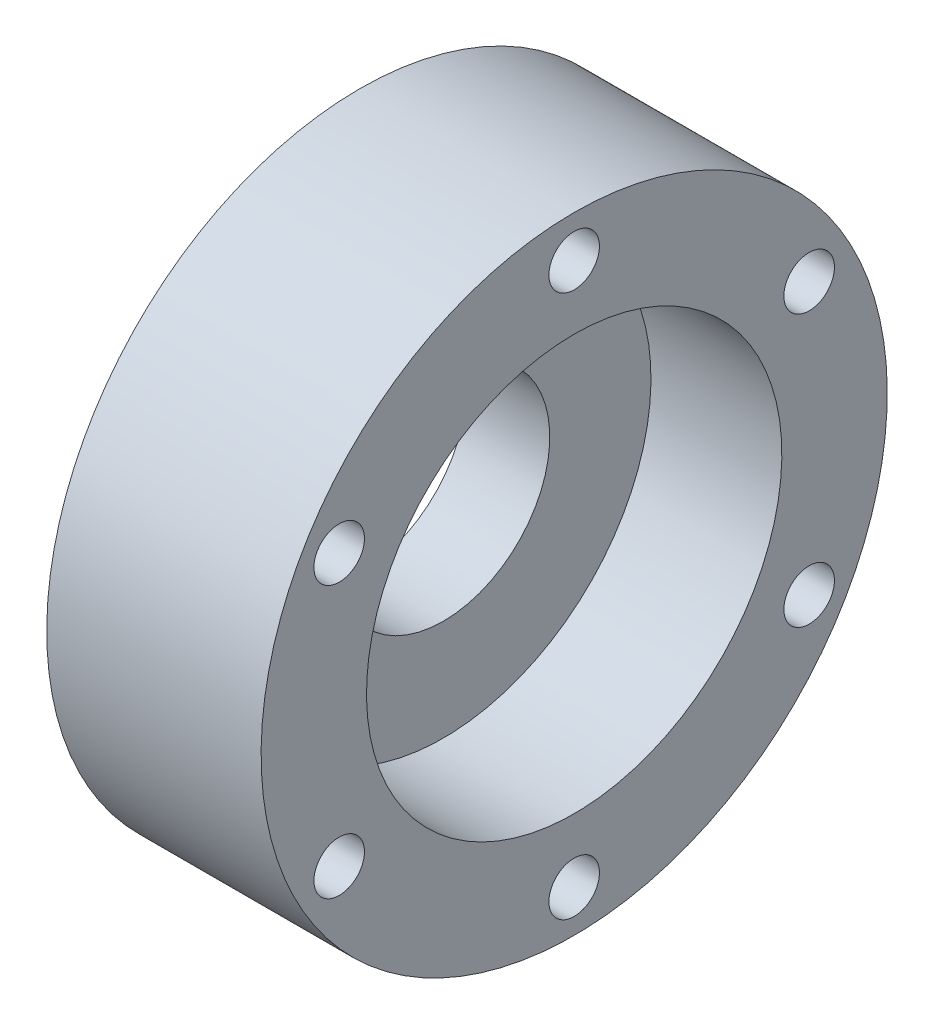
SolidWorks part; units mm, degrees
material "6061 Alloy"
ref_plane "Front Plane" through (0, 0, 0) normal (0, 0, 1) x (1, 0, 0)
ref_plane "Top Plane" through (0, 0, 0) normal (0, 1, 0) x (1, 0, 0)
ref_plane "Right Plane" through (0, 0, 0) normal (1, 0, 0) x (0, 0, -1)
sketch "Sketch1" plane through (0, 0, 0) normal (0, 0, 1) x (1, 0, 0)
  line L0 (0, 0) -> (0, 19.05)
  line L1 (0, 19.05) -> (13.0429, 19.05)
  line L2 (13.0429, 19.05) -> (13.0429, 12.6365)
  line L3 (13.0429, 12.6365) -> (5.08, 12.6365)
  line L4 (5.08, 12.6365) -> (5.08, 0)
  line L5 (5.08, 0) -> (0, 0) construction
  line L6 (0, 0) -> (5.08, 0)
  dimension "D1" = 38.1
  dimension "D2" = 6.4135
  dimension "D3" = 13.0429
  dimension "D4" = 5.08
revolve "Revolve1" add sketch "Sketch1" angle 360 about L5
sketch "Sketch2" plane through (0, 0, 0) normal (-1, 0, 0) x (0, 0, 1)
  circle A0 centre (0, 0) radius 6.477
  dimension "D1" = 12.954
extrude "Cut-Extrude1" cut sketch "Sketch2" against normal through all
sketch "Sketch3" plane through (0, 0, 0) normal (-1, 0, 0) x (0, 0, 1)
  circle A0 centre (0, 16.51) radius 1.5381
  circle A1 centre (0, 0) radius 19.05 construction
  circle A2 centre (14.2981, 8.255) radius 1.5381
  circle A3 centre (14.2981, -8.255) radius 1.5381
  circle A4 centre (0, -16.51) radius 1.5381
  circle A5 centre (-14.2981, -8.255) radius 1.5381
  circle A6 centre (-14.2981, 8.255) radius 1.5381
  point P17 (0, 0)
  dimension "D1" = 16.51
  dimension "D2" = 6
extrude "Cut-Extrude2" cut sketch "Sketch3" against normal through all
equation "\"D1@Sketch3\"=(1.5/2)-0.1"
equation "\"D3@Sketch1\"=0.3135+0.2"
equation "\"D2@Sketch1\"=(1.5-0.995)/2"
